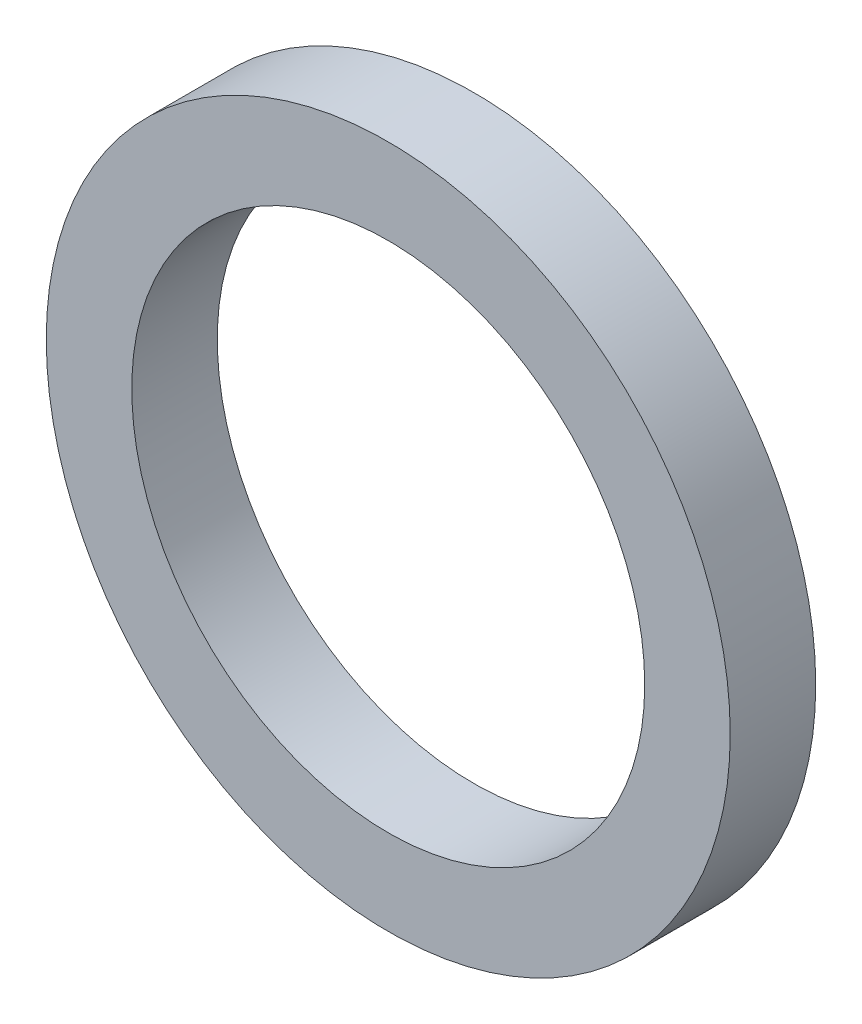
SolidWorks part; units mm, degrees
material "Polyurethane Foam Flexible"
ref_plane "Front Plane" through (0, 0, 0) normal (0, 0, 1) x (1, 0, 0)
ref_plane "Top Plane" through (0, 0, 0) normal (0, 1, 0) x (1, 0, 0)
ref_plane "Right Plane" through (0, 0, 0) normal (1, 0, 0) x (0, 0, -1)
sketch "Sketch1" plane through (0, 0, 0) normal (0, 0, 1) x (1, 0, 0)
  circle A0 centre (0, 0) radius 12.7
  dimension "D1" = 25.4
extrude "Boss-Extrude1" add sketch "Sketch1" along normal blind 3.175
sketch "Sketch2" plane through (0, 0, 3.175) normal (0, 0, 1) x (1, 0, 0)
  circle A0 centre (0, 0) radius 9.525
  dimension "D1" = 19.05
extrude "Cut-Extrude1" cut sketch "Sketch2" against normal through all
